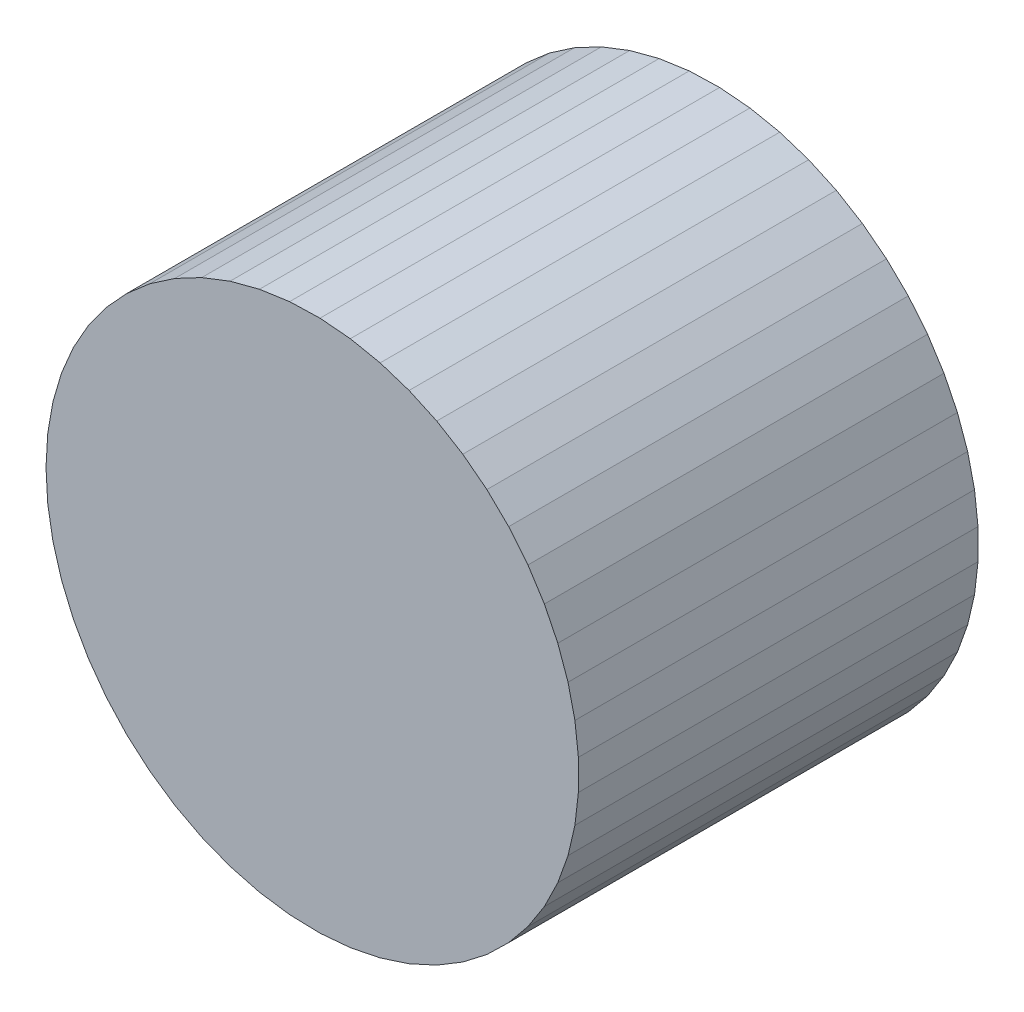
SolidWorks part; units mm, degrees
ref_plane "Front Plane" through (0, 0, 0) normal (0, 0, 1) x (1, 0, 0)
ref_plane "Top Plane" through (0, 0, 0) normal (0, 1, 0) x (1, 0, 0)
ref_plane "Right Plane" through (0, 0, 0) normal (1, 0, 0) x (0, 0, -1)
sketch "Biên dạng ngoài theo phôi gốc" plane through (0, 0, 0) normal (0, 0, 1) x (1, 0, 0)
  line L0 (-20, 0) -> (-19.8696, -2.2798)
  line L1 (-19.8696, -2.2798) -> (-19.4802, -4.5299)
  line L2 (-19.4802, -4.5299) -> (-18.8369, -6.721)
  line L3 (-18.8369, -6.721) -> (-17.948, -8.8244)
  line L4 (-17.948, -8.8244) -> (-16.8251, -10.8128)
  line L5 (-16.8251, -10.8128) -> (-15.4828, -12.6602)
  line L6 (-15.4828, -12.6602) -> (-13.9388, -14.3426)
  line L7 (-13.9388, -14.3426) -> (-12.213, -15.838)
  line L8 (-12.213, -15.838) -> (-10.3279, -17.127)
  line L9 (-10.3279, -17.127) -> (-8.3083, -18.1926)
  line L10 (-8.3083, -18.1926) -> (-6.1803, -19.0211)
  line L11 (-6.1803, -19.0211) -> (-3.9718, -19.6017)
  line L12 (-3.9718, -19.6017) -> (-1.7115, -19.9266)
  line L13 (-1.7115, -19.9266) -> (0.5711, -19.9918)
  line L14 (0.5711, -19.9918) -> (2.8463, -19.7964)
  line L15 (2.8463, -19.7964) -> (5.0844, -19.3429)
  line L16 (5.0844, -19.3429) -> (7.2562, -18.6373)
  line L17 (7.2562, -18.6373) -> (9.3333, -17.6887)
  line L18 (9.3333, -17.6887) -> (11.2889, -16.5094)
  line L19 (11.2889, -16.5094) -> (13.0972, -15.115)
  line L20 (13.0972, -15.115) -> (14.7348, -13.5235)
  line L21 (14.7348, -13.5235) -> (16.1803, -11.7557)
  line L22 (16.1803, -11.7557) -> (17.4149, -9.8347)
  line L23 (17.4149, -9.8347) -> (18.4225, -7.7854)
  line L24 (18.4225, -7.7854) -> (19.1899, -5.6347)
  line L25 (19.1899, -5.6347) -> (19.7071, -3.4104)
  line L26 (19.7071, -3.4104) -> (19.9674, -1.1418)
  line L27 (19.9674, -1.1418) -> (19.9674, 1.1418)
  line L28 (19.9674, 1.1418) -> (19.7071, 3.4104)
  line L29 (19.7071, 3.4104) -> (19.1899, 5.6347)
  line L30 (19.1899, 5.6347) -> (18.4225, 7.7854)
  line L31 (18.4225, 7.7854) -> (17.4149, 9.8347)
  line L32 (17.4149, 9.8347) -> (16.1803, 11.7557)
  line L33 (16.1803, 11.7557) -> (14.7348, 13.5235)
  line L34 (14.7348, 13.5235) -> (13.0972, 15.115)
  line L35 (13.0972, 15.115) -> (11.2889, 16.5094)
  line L36 (11.2889, 16.5094) -> (9.3333, 17.6887)
  line L37 (9.3333, 17.6887) -> (7.2562, 18.6373)
  line L38 (7.2562, 18.6373) -> (5.0844, 19.3429)
  line L39 (5.0844, 19.3429) -> (2.8463, 19.7964)
  line L40 (2.8463, 19.7964) -> (0.5711, 19.9918)
  line L41 (0.5711, 19.9918) -> (-1.7115, 19.9266)
  line L42 (-1.7115, 19.9266) -> (-3.9718, 19.6017)
  line L43 (-3.9718, 19.6017) -> (-6.1803, 19.0211)
  line L44 (-6.1803, 19.0211) -> (-8.3083, 18.1926)
  line L45 (-8.3083, 18.1926) -> (-10.3279, 17.127)
  line L46 (-10.3279, 17.127) -> (-12.213, 15.838)
  line L47 (-12.213, 15.838) -> (-13.9388, 14.3426)
  line L48 (-13.9388, 14.3426) -> (-15.4828, 12.6602)
  line L49 (-15.4828, 12.6602) -> (-16.8251, 10.8128)
  line L50 (-16.8251, 10.8128) -> (-17.948, 8.8244)
  line L51 (-17.948, 8.8244) -> (-18.8369, 6.721)
  line L52 (-18.8369, 6.721) -> (-19.4802, 4.5299)
  line L53 (-19.4802, 4.5299) -> (-19.8696, 2.2798)
  line L54 (-19.8696, 2.2798) -> (-20, 0)
extrude "Thân ngoài" add sketch "Biên dạng ngoài theo phôi gốc" along normal blind 30
sketch "Biên dạng trong cách thành ngoài 0,3 mm" plane through (0, 0, 0) normal (0, 0, 1) x (1, 0, 0)
  line L0 (-19.5711, -2.2456) -> (-19.1876, -4.4619)
  line L1 (-19.1876, -4.4619) -> (-18.5539, -6.62)
  line L2 (-18.5539, -6.62) -> (-17.6783, -8.6918)
  line L3 (-17.6783, -8.6918) -> (-16.5723, -10.6504)
  line L4 (-16.5723, -10.6504) -> (-15.2502, -12.47)
  line L5 (-15.2502, -12.47) -> (-13.7293, -14.1271)
  line L6 (-13.7293, -14.1271) -> (-12.0295, -15.6001)
  line L7 (-12.0295, -15.6001) -> (-10.1728, -16.8697)
  line L8 (-10.1728, -16.8697) -> (-8.1835, -17.9193)
  line L9 (-8.1835, -17.9193) -> (-6.0875, -18.7353)
  line L10 (-6.0875, -18.7353) -> (-3.9121, -19.3071)
  line L11 (-3.9121, -19.3071) -> (-1.6858, -19.6272)
  line L12 (-1.6858, -19.6272) -> (0.5625, -19.6915)
  line L13 (0.5625, -19.6915) -> (2.8035, -19.499)
  line L14 (2.8035, -19.499) -> (5.008, -19.0523)
  line L15 (5.008, -19.0523) -> (7.1471, -18.3573)
  line L16 (7.1471, -18.3573) -> (9.1931, -17.4229)
  line L17 (9.1931, -17.4229) -> (11.1193, -16.2614)
  line L18 (11.1193, -16.2614) -> (12.9004, -14.8879)
  line L19 (12.9004, -14.8879) -> (14.5134, -13.3203)
  line L20 (14.5134, -13.3203) -> (15.9372, -11.5791)
  line L21 (15.9372, -11.5791) -> (17.1533, -9.6869)
  line L22 (17.1533, -9.6869) -> (18.1457, -7.6684)
  line L23 (18.1457, -7.6684) -> (18.9015, -5.55)
  line L24 (18.9015, -5.55) -> (19.411, -3.3592)
  line L25 (19.411, -3.3592) -> (19.6674, -1.1246)
  line L26 (19.6674, -1.1246) -> (19.6674, 1.1246)
  line L27 (19.6674, 1.1246) -> (19.411, 3.3592)
  line L28 (19.411, 3.3592) -> (18.9015, 5.55)
  line L29 (18.9015, 5.55) -> (18.1457, 7.6684)
  line L30 (18.1457, 7.6684) -> (17.1533, 9.6869)
  line L31 (17.1533, 9.6869) -> (15.9372, 11.5791)
  line L32 (15.9372, 11.5791) -> (14.5134, 13.3203)
  line L33 (14.5134, 13.3203) -> (12.9004, 14.8879)
  line L34 (12.9004, 14.8879) -> (11.1193, 16.2614)
  line L35 (11.1193, 16.2614) -> (9.1931, 17.4229)
  line L36 (9.1931, 17.4229) -> (7.1471, 18.3573)
  line L37 (7.1471, 18.3573) -> (5.008, 19.0523)
  line L38 (5.008, 19.0523) -> (2.8035, 19.499)
  line L39 (2.8035, 19.499) -> (0.5625, 19.6915)
  line L40 (0.5625, 19.6915) -> (-1.6858, 19.6272)
  line L41 (-1.6858, 19.6272) -> (-3.9121, 19.3071)
  line L42 (-3.9121, 19.3071) -> (-6.0875, 18.7353)
  line L43 (-6.0875, 18.7353) -> (-8.1835, 17.9193)
  line L44 (-8.1835, 17.9193) -> (-10.1728, 16.8697)
  line L45 (-10.1728, 16.8697) -> (-12.0295, 15.6001)
  line L46 (-12.0295, 15.6001) -> (-13.7293, 14.1271)
  line L47 (-13.7293, 14.1271) -> (-15.2502, 12.47)
  line L48 (-15.2502, 12.47) -> (-16.5723, 10.6504)
  line L49 (-16.5723, 10.6504) -> (-17.6783, 8.6918)
  line L50 (-17.6783, 8.6918) -> (-18.5539, 6.62)
  line L51 (-18.5539, 6.62) -> (-19.1876, 4.4619)
  line L52 (-19.1876, 4.4619) -> (-19.5711, 2.2456)
  line L53 (-19.5711, 2.2456) -> (-19.6995, 0)
  line L54 (-19.6995, 0) -> (-19.5711, -2.2456)
extrude "Khoang rỗng kín" cut sketch "Biên dạng trong cách thành ngoài 0,3 mm" along normal blind 29 from offset 0.5
